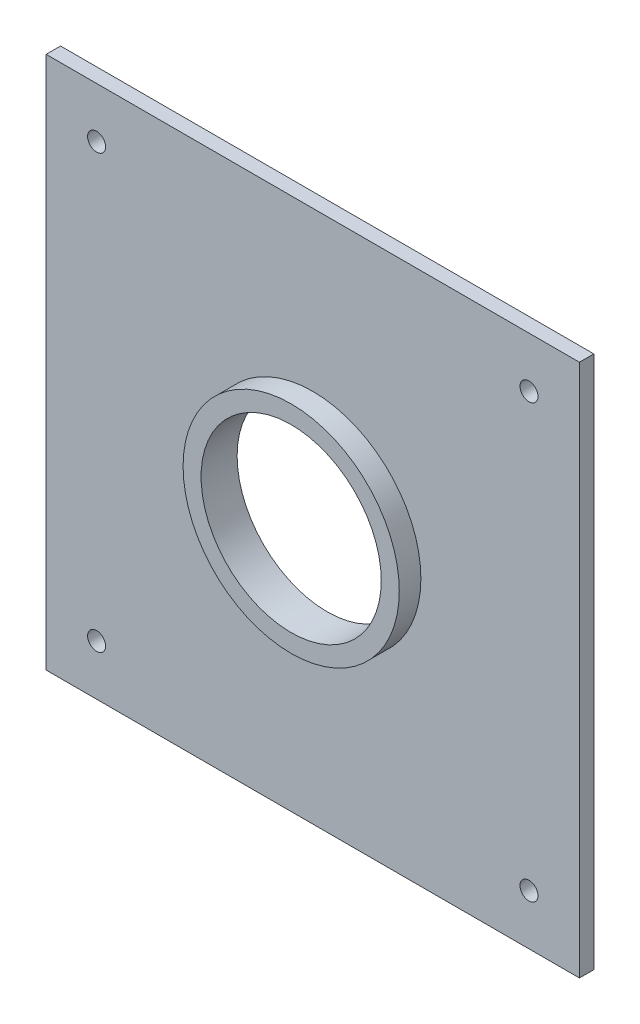
SolidWorks part; units mm, degrees
ref_plane "正面" through (0, 0, 0) normal (0, 0, 1) x (1, 0, 0)
ref_plane "平面" through (0, 0, 0) normal (0, 1, 0) x (1, 0, 0)
ref_plane "右側面" through (0, 0, 0) normal (1, 0, 0) x (0, 0, -1)
sketch "ｽｹｯﾁ2" plane through (0, 0, 0) normal (0, 0, 1) x (1, 0, 0)
  line L1 (0, 0) -> (-74, 0)
  line L2 (0, 0) -> (0, -74)
  line L3 (0, -74) -> (-74, -74)
  line L4 (-74, 0) -> (-74, -74)
  dimension "D1" = 74
  dimension "D2" = 74
extrude "ﾎﾞｽ - 押し出し1" add sketch "ｽｹｯﾁ2" along normal blind 2
sketch "ｽｹｯﾁ3" plane through (0, 0, 2) normal (0, 0, 1) x (1, 0, 0)
  line L0 (1.1, 0) -> (-1.1, 0) construction
  line L1 (-74, 0) -> (-74, -74) construction
  circle A0 centre (-37, -37) radius 15
  dimension "D3" = 30
  dimension "D1" = 37
  dimension "D2" = 37
extrude "ﾎﾞｽ - 押し出し2" add sketch "ｽｹｯﾁ3" along normal blind 3
sketch "ｽｹｯﾁ4" plane through (0, 0, 5) normal (0, 0, 1) x (1, 0, 0)
  circle A0 centre (-37, -37) radius 12.5
  dimension "D1" = 25
extrude "ｶｯﾄ - 押し出し1" cut sketch "ｽｹｯﾁ4" against normal blind 10 contours A0
hole_wizard "M3x0.5 ねじ穴1" positions "ｽｹｯﾁ5" profile "ｽｹｯﾁ6" tap size "M3x0.5" standard "JIS" end condition through all
sketch "ｽｹｯﾁ5" plane through (0, 0, 2) normal (0, 0, 1) x (1, 0, 0)
  line L0 (-74, -74) -> (0, -74) construction
  line L1 (-74, 0) -> (-74, -74) construction
  line L2 (0, -74) -> (0, 0) construction
  point P0 (-67, -67)
  point P2 (-7, -67)
  dimension "D1" = 7
  dimension "D2" = 7
  dimension "D3" = 7
  dimension "D4" = 7
sketch "ｽｹｯﾁ6" plane through (-67, -67, 2) normal (1, 0, 0) x (0, -1, 0)
  line L0 (0, 0) -> (0, 2)
  line L1 (0, 2) -> (1.25, 2)
  line L2 (1.25, 2) -> (1.25, 0)
  line L5 (1.25, 0) -> (0, 0)
  line L11 (0, -6.35) -> (0, 107.95) construction
  dimension "次ｻｰﾌｪｽまでのねじ下穴ﾄﾞﾘﾙ直径" = 2.5
  dimension "次ｻｰﾌｪｽまでのねじ下穴ﾄﾞﾘﾙの深さ" = 2
cosmetic thread "穴のねじ山1" parameters "D2"=3
cosmetic thread "穴のねじ山2" parameters "D2"=3
ref_plane "平面1" through (0, -37, 0) normal (0, 1, 0) x (1, 0, 0)
mirror "ﾐﾗｰ1" about plane through (0, -37, 0) normal (0, 1, 0) of "M3x0.5 ねじ穴1"
